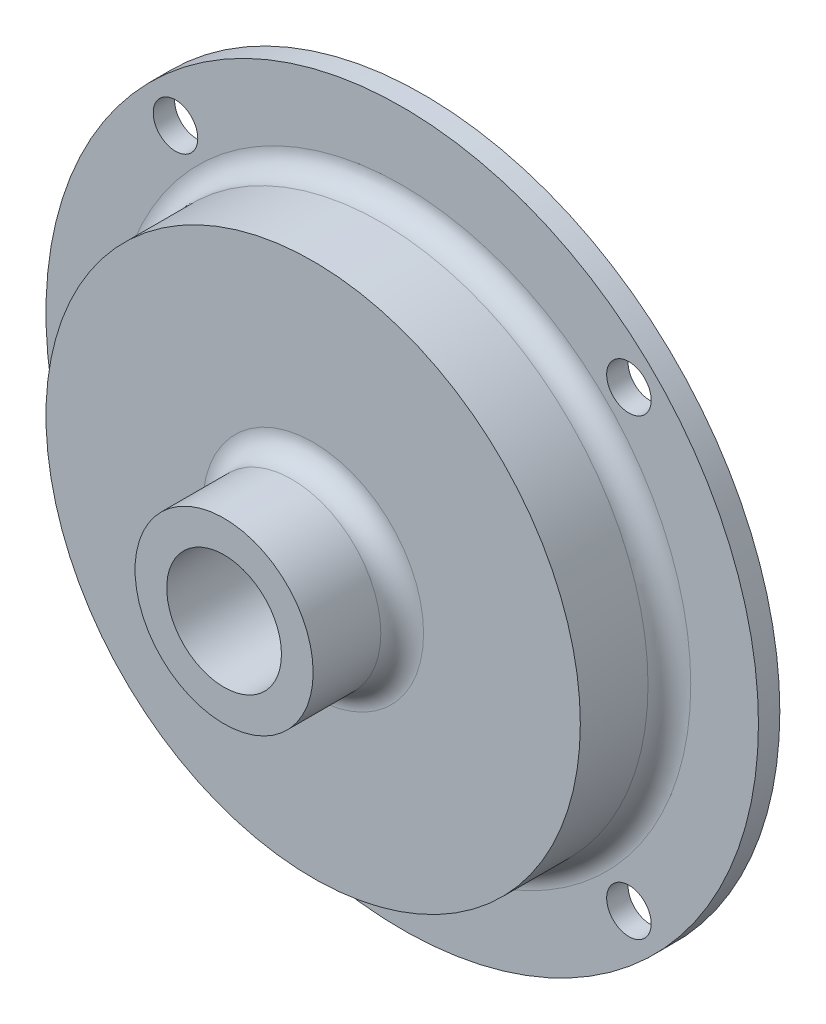
SolidWorks part; units mm, degrees
material "PW40:6:Sc:0:Re:24:"
ref_plane "Front" through (0, 0, 0) normal (0, 0, 1) x (1, 0, 0)
ref_plane "Top" through (0, 0, 0) normal (0, 1, 0) x (1, 0, 0)
ref_plane "Right" through (0, 0, 0) normal (1, 0, 0) x (0, 0, -1)
other "Configuration Table"
sketch "Sketch1" plane through (0, 0, 0) normal (0, 0, 1) x (1, 0, 0)
  line L0 (0, 0) -> (50, 0) construction
  line L1 (0, 0) -> (35.3553, 35.3553) construction
  line L2 (0, 0) -> (-35.3553, 35.3553) construction
  circle A0 centre (0, 0) radius 50
  circle A1 centre (0, 0) radius 45 construction
  circle A2 centre (31.8198, 31.8198) radius 3.125
  circle A4 centre (-31.8198, -31.8198) radius 3.125
  circle A6 centre (31.8198, -31.8198) radius 3.125
  circle A7 centre (-31.8198, 31.8198) radius 3.125
  dimension "D1" = 100
  dimension "D3" = 6.25
  dimension "D4" = 90
  dimension "D2" = 45
extrude "Base-Extrude" add sketch "Sketch1" along normal blind 3
sketch "Sketch2" plane through (0, 0, 3) normal (0, 0, 1) x (1, 0, 0)
  circle A0 centre (0, 0) radius 37.5
  dimension "D1" = 75
extrude "Boss-Extrude1" add sketch "Sketch2" along normal blind 12.5
sketch "Sketch3" plane through (0, 0, 15.5) normal (0, 0, 1) x (1, 0, 0)
  circle A0 centre (0, 0) radius 12.5
  dimension "D1" = 25
extrude "Boss-Extrude2" add sketch "Sketch3" along normal blind 12.5
fillet "Fillet1" radius 3 2 edges at (37.5, 0, 3) (12.5, 0, 15.5)
sketch "Sketch4" plane through (0, 0, 28) normal (0, 0, 1) x (1, 0, 0)
  circle A0 centre (0, 0) radius 8.05
  dimension "D1" = 16.1
extrude "Cut-Extrude1" cut sketch "Sketch4" against normal through all
